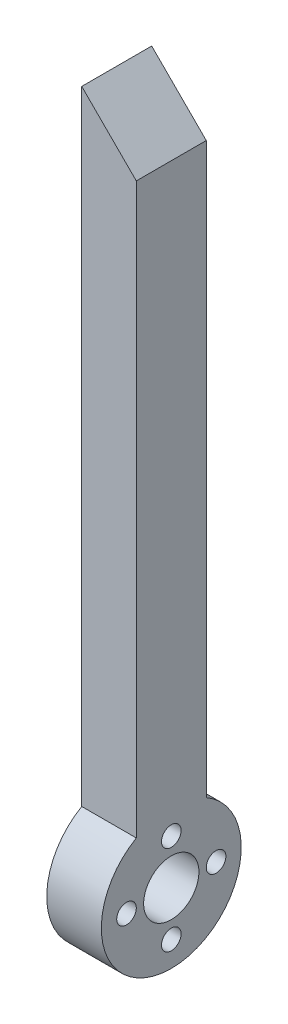
SolidWorks part; units mm, degrees
ref_plane "Front Plane" through (0, 0, 0) normal (0, 0, 1) x (1, 0, 0)
ref_plane "Top Plane" through (0, 0, 0) normal (0, 1, 0) x (1, 0, 0)
ref_plane "Right Plane" through (0, 0, 0) normal (1, 0, 0) x (0, 0, -1)
sketch "Sketch1" plane through (0, 0, 0) normal (1, 0, 0) x (0, 0, -1)
  line L0 (0, -61.7985) -> (-27.0167, -61.7985) construction
  line L2 (-6.35, -50.8) -> (-6.35, 52.5015)
  line L3 (-6.35, 52.5015) -> (6.35, 52.5015)
  line L4 (6.35, -50.8) -> (6.35, 52.5015)
  line L5 (0, -61.7985) -> (12.7, -61.7985) construction
  line L6 (-27.0167, -61.7985) -> (-27.0167, 52.5015) construction
  line L7 (-6.35, 52.5015) -> (-27.0167, 52.5015) construction
  line L8 (0, 55) -> (0, -55) construction
  line L9 (-6.35, -50.8) -> (0, -61.7985) construction
  line L10 (0, -61.7985) -> (6.35, -50.8) construction
  line L11 (0, -49.0985) -> (-6.35, -49.0985) construction
  circle A0 centre (0, -61.7985) radius 5.0165
  arc A1 (-6.35, -50.8) -> (6.35, -50.8) centre (0, -61.7985) ccw
  circle A2 centre (-8.128, -61.7985) radius 1.778
  circle A6 centre (8.128, -61.7985) radius 1.778
  circle A7 centre (0, -53.6705) radius 1.778
  circle A8 centre (0, -69.9265) radius 1.778
  arc A10 (6.35, -50.8) -> (-6.35, -50.8) centre (0, -61.7985) ccw construction
  point P0 (0, 0)
  point P22 (0, -69.9265)
  dimension "D3" = 10.033
  dimension "D4" = 25.4
  dimension "D5" = 101.6
  dimension "D1" = 3.556
  dimension "D7" = 3.556
  dimension "D9" = 3.556
  dimension "D10" = 3.556
  dimension "D2" = 12.7
  dimension "D6" = 8.128
  dimension "D8" = 8.128
  dimension "D11" = 8.128
  dimension "D12" = 8.128
extrude "Boss-Extrude1" add sketch "Sketch1" along normal blind 9.906
sketch "Sketch2" plane through (0, 0, 6.35) normal (0, 0, 1) x (1, 0, 0)
  line L0 (9.906, 52.5015) -> (0, 52.5015)
  line L1 (0, -55) -> (0, 55) construction
  line L2 (9.906, 52.5015) -> (0, 52.5015) construction
  line L3 (0, 52.5015) -> (0, 62.4075)
  line L4 (9.906, 52.5015) -> (0, 62.4075)
  dimension "D1" = 9.906
extrude "Boss-Extrude2" add sketch "Sketch2" against normal up to surface (12.7 mm away) up to face at (4.953, 0.8507, -6.35)
